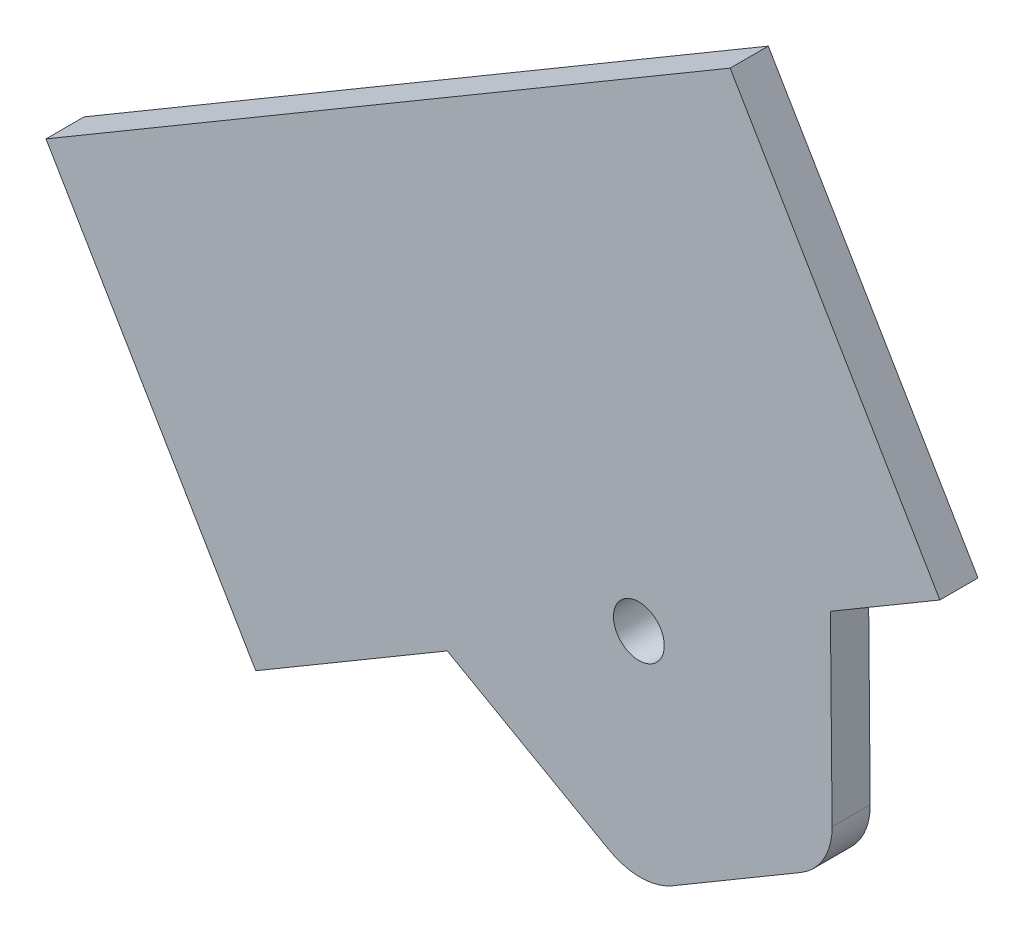
SolidWorks part; units mm, degrees
ref_plane "Front Plane" through (0, 0, 0) normal (0, 0, 1) x (1, 0, 0)
ref_plane "Top Plane" through (0, 0, 0) normal (0, 1, 0) x (1, 0, 0)
ref_plane "Right Plane" through (0, 0, 0) normal (1, 0, 0) x (0, 0, -1)
sketch "Sketch1" plane through (0, 0, 0) normal (0, 0, 1) x (1, 0, 0)
  line L8 (95.687, 386.1036) -> (62.6758, 442.0969)
  line L9 (78.4583, 375.9463) -> (95.687, 386.1036)
  line L10 (78.7244, 346.721) -> (78.4583, 375.9463)
  line L11 (53.6002, 326.1046) -> (73.8035, 338.0155)
  line L12 (18.1578, 340.3957) -> (43.6007, 326.0135)
  line L13 (-11.9925, 322.6204) -> (18.1578, 340.3957)
  line L14 (-45.0038, 378.6138) -> (-11.9925, 322.6204)
  line L15 (62.6758, 442.0969) -> (-45.0038, 378.6138)
  circle A3 centre (48.308, 358.171) radius 4
  arc A4 (73.8035, 338.0155) -> (78.7244, 346.721) centre (68.7249, 346.6299) ccw
  arc A5 (43.6007, 326.0135) -> (53.6002, 326.1046) centre (48.5216, 334.719) ccw
  dimension "D7" = 10
  dimension "D12" = 8
  dimension "D1" = 65
  dimension "D2" = 322.6204
  dimension "D3" = 11.9925
  dimension "D4" = 23.453
  dimension "D5" = 125
  dimension "D6" = 29.2253
  dimension "D8" = 20
  dimension "D9" = 35
  dimension "D10" = 60
  dimension "D11" = 60
  dimension "D13" = 35
  dimension "D14" = 35
  dimension "D15" = 120
  dimension "D16" = 90
  dimension "D17" = 120
  dimension "D18" = 90
  dimension "D19" = 90
extrude "Boss-Extrude1" add sketch "Sketch1" along normal blind 6 separate body
